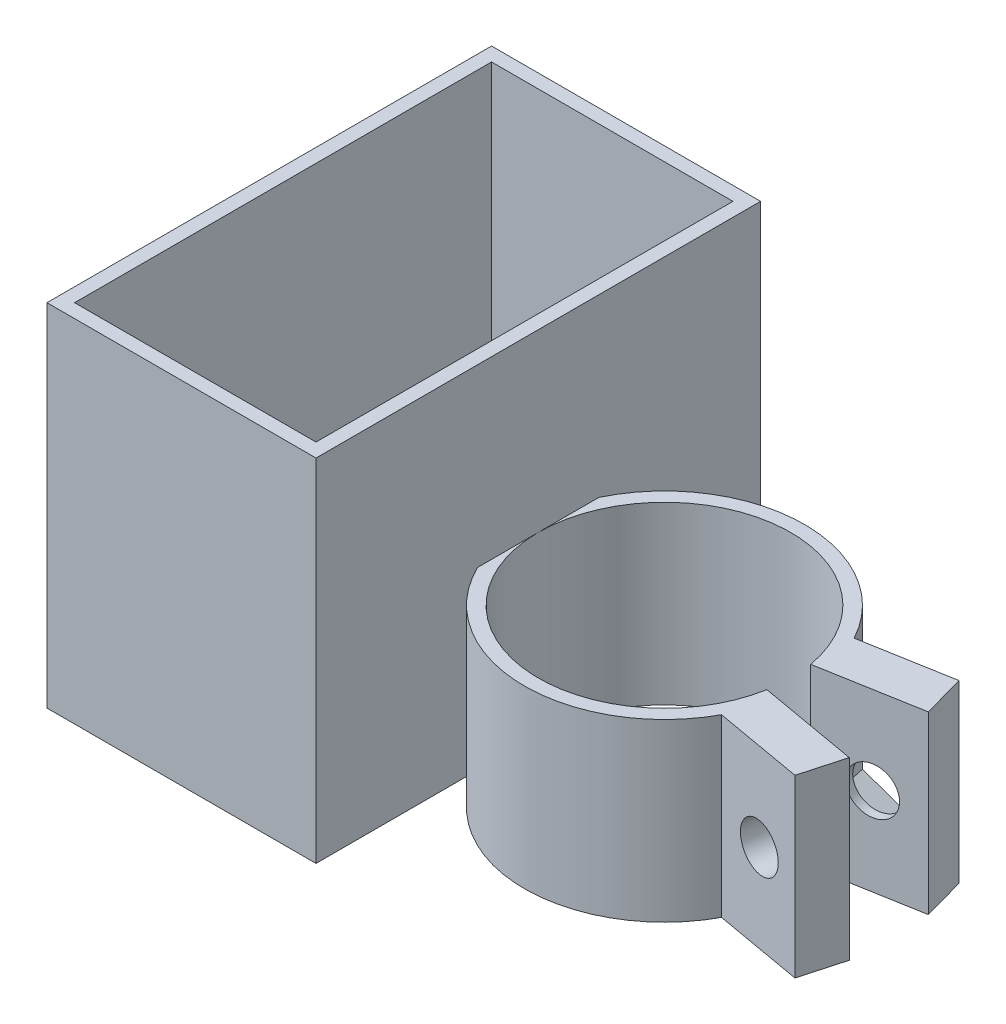
SolidWorks part; units mm, degrees
ref_plane "Front Plane" through (0, 0, 0) normal (0, 0, 1) x (1, 0, 0)
ref_plane "Top Plane" through (0, 0, 0) normal (0, 1, 0) x (1, 0, 0)
ref_plane "Right Plane" through (0, 0, 0) normal (1, 0, 0) x (0, 0, -1)
sketch "Sketch1" plane through (0, 0, 0) normal (0, 1, 0) x (1, 0, 0)
  line L1 (0, 0) -> (32.4556, -5.7228)
  line L2 (0, 0) -> (32.4556, 5.7228)
  line L3 (30.7447, -11.8691) -> (17.8403, -9.5937)
  line L4 (0, 0) -> (20.2562, 0) construction
  line L5 (30.7447, 11.8691) -> (17.8403, 9.5937)
  line L7 (32.4556, 5.7228) -> (30.7447, 11.8691)
  line L8 (30.7447, -11.8691) -> (32.4556, -5.7228)
  line L9 (17.8403, -9.5937) -> (19.9485, -3.5175)
  line L10 (19.9485, 3.5175) -> (17.8403, 9.5937)
  circle A0 centre (0, 0) radius 18.2562
  circle A1 centre (0, 0) radius 20.2562
  circle A2 centre (0, 0) radius 32.9562 construction
  dimension "D1" = 36.5125
  dimension "D2" = 2
  dimension "D5" = 10
  dimension "D3" = 12.7
  dimension "D4" = 6.35
  dimension "D6" = 10
extrude "Boss-Extrude1" add sketch "Sketch1" along normal blind 25.4 contours L10 A1 L9 L1 A0 L2 | A1 L2 L7 L5 | A1 L3 L8 L1 | L9 A1 | L10 A1
sketch "Sketch3" plane through (-1.1027, 0, 6.2535) normal (-0.1736, 0, 0.9848) x (0.9848, 0, 0.1736)
  line L0 (32.3387, 25.4) -> (32.3387, 0) construction
  line L1 (32.3387, 25.4) -> (19.2352, 25.4) construction
  circle A0 centre (25.9887, 12.7) radius 3.3734
  dimension "D1" = 6.7469
  dimension "D2" = 6.35
  dimension "D3" = 12.7
sketch "Sketch4" plane through (-1.1027, 0, -6.2535) normal (-0.1736, 0, -0.9848) x (-0.9848, 0, 0.1736)
  line L0 (-32.3387, 25.4) -> (-32.3387, 0) construction
  line L1 (-32.3387, 25.4) -> (-19.2352, 25.4) construction
  circle A0 centre (-25.9887, 12.7) radius 3.3734
  point P6 (-22.813, 25.4)
  dimension "D3" = 6.7469
  dimension "D1" = 6.35
  dimension "D2" = 12.7
extrude "Cut-Extrude1" cut sketch "Sketch3" against normal up to next
extrude "Cut-Extrude2" cut sketch "Sketch4" against normal up to next
sketch "Sketch6" plane through (0, 0, 0) normal (0, -1, 0) x (1, 0, 0)
  line L0 (-20.2562, -30.1625) -> (-20.2562, 30.1625)
  line L1 (-18.2562, -32.1625) -> (-57.1812, -32.1625)
  line L2 (-18.2562, -32.1625) -> (-18.2562, 32.1625)
  line L3 (-18.2562, 32.1625) -> (-57.1812, 32.1625)
  line L4 (-57.1812, -32.1625) -> (-57.1812, 32.1625)
  line L5 (-20.2562, 30.1625) -> (-55.1812, 30.1625)
  line L6 (-55.1812, -30.1625) -> (-55.1812, 30.1625)
  line L7 (-20.2562, -30.1625) -> (-55.1812, -30.1625)
  arc A2 (17.8403, 9.5937) -> (17.8403, -9.5937) centre (0, 0) ccw construction
  point P8 (-20.2562, 0)
  dimension "D2" = 60.325
  dimension "D3" = 34.925
  dimension "D1" = 2
extrude "Boss-Extrude4" add sketch "Sketch6" against normal blind 50.8
sketch "Sketch7" plane through (0, 50.8, 0) normal (0, 1, 0) x (1, 0, 0)
  line L4 (-18.2562, -32.1625) -> (-18.2562, 32.1625)
  line L5 (-18.2562, 32.1625) -> (-57.1812, 32.1625)
  line L6 (-57.1812, 32.1625) -> (-57.1812, -32.1625)
  line L7 (-57.1812, -32.1625) -> (-18.2562, -32.1625)
  line L8 (-18.2562, -32.1625) -> (-18.2562, 32.1625)
  line L9 (-18.2562, 32.1625) -> (-57.1812, 32.1625)
  line L10 (-57.1812, 32.1625) -> (-57.1812, -32.1625)
  line L11 (-57.1812, -32.1625) -> (-18.2562, -32.1625)
  dimension "D1" = 0
sketch "Sketch8" plane through (-1.1027, 0, -6.2535) normal (-0.1736, 0, -0.9848) x (-0.9848, 0, 0.1736)
  line L1 (-20.2737, 9.4004) -> (-20.2737, 15.9996)
  line L2 (-20.2737, 15.9996) -> (-25.9887, 19.2991)
  line L3 (-25.9887, 19.2991) -> (-31.7037, 15.9996)
  line L4 (-31.7037, 15.9996) -> (-31.7037, 9.4004)
  line L5 (-31.7037, 9.4004) -> (-25.9887, 6.1009)
  line L6 (-25.9887, 6.1009) -> (-20.2737, 9.4004)
  circle A0 centre (-25.9887, 12.7) radius 5.715 construction
  dimension "D1" = 11.43
extrude "Cut-Extrude3" cut sketch "Sketch8" against normal blind 5.08 draft 4.3
sketch "Sketch9" plane through (0, 0, 0) normal (0, -1, 0) x (1, 0, 0)
  line L0 (-20.2562, -30.1625) -> (-20.2562, 30.1625) construction
  line L1 (-55.1812, -30.1625) -> (-20.2562, -30.1625) construction
  line L2 (-55.1812, 30.1625) -> (-55.1812, -30.1625) construction
  line L3 (-20.2562, 30.1625) -> (-55.1812, 30.1625) construction
  line L4 (-20.2562, -30.1625) -> (-20.2562, 30.1625)
  line L5 (-55.1812, -30.1625) -> (-20.2562, -30.1625)
  line L6 (-55.1812, 30.1625) -> (-55.1812, -30.1625)
  line L7 (-20.2562, 30.1625) -> (-55.1812, 30.1625)
extrude "Boss-Extrude6" add sketch "Sketch9" against normal blind 3.175
